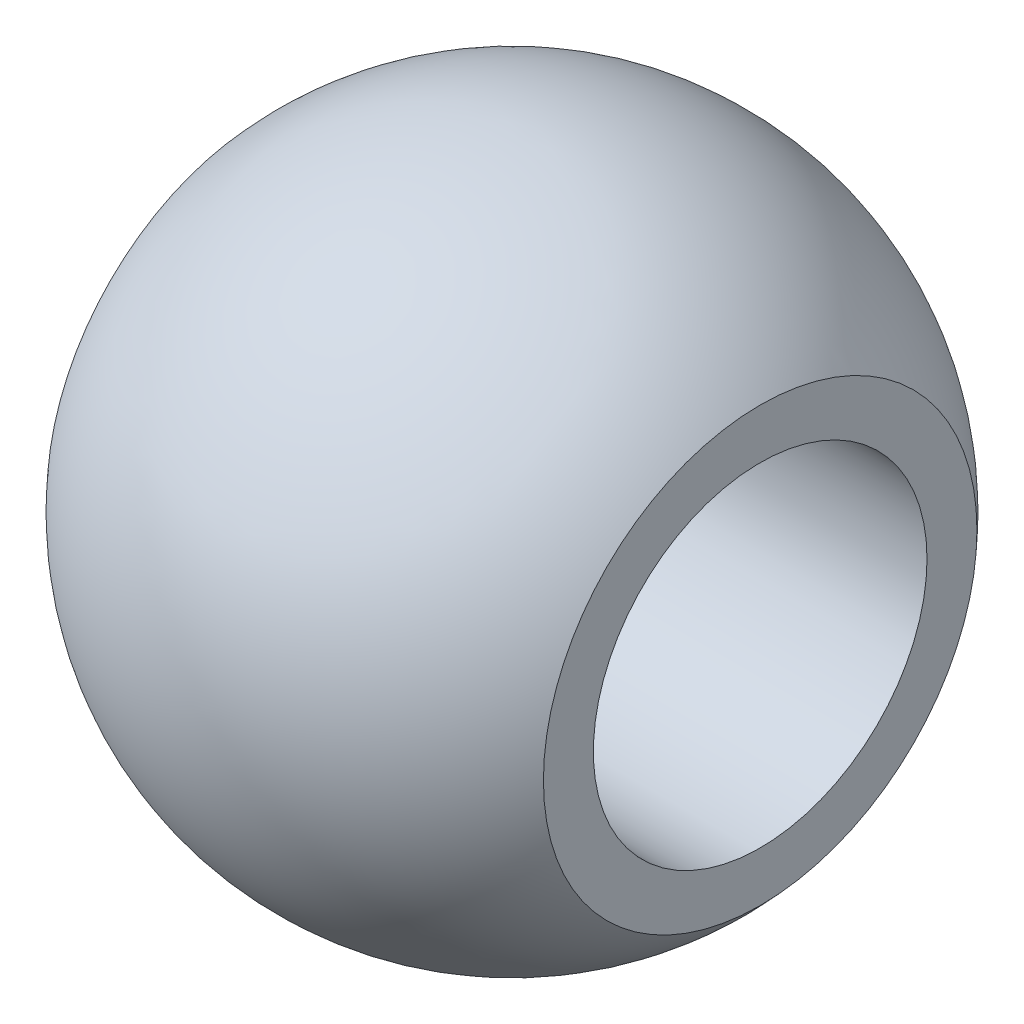
SolidWorks part; units mm, degrees
ref_plane "Front Plane" through (0, 0, 0) normal (0, 0, 1) x (1, 0, 0)
ref_plane "Top Plane" through (0, 0, 0) normal (0, 1, 0) x (1, 0, 0)
ref_plane "Right Plane" through (0, 0, 0) normal (1, 0, 0) x (0, 0, -1)
sketch "Sketch1" plane through (0, 0, 0) normal (1, 0, 0) x (0, 0, -1)
  line L0 (0, -7.9) -> (0, 0)
  line L1 (0, 0) -> (0, 7.9)
  arc A0 (0, 7.9) -> (0, -7.9) centre (0, 0) ccw
  dimension "D1" = 15.8
revolve "Revolve1" add sketch "Sketch1" angle 360 about L1
ref_plane "Plane1" through (5.95, 0, 0) normal (1, 0, 0) x (0, 0, -1)
ref_plane "Plane2" through (-5.95, 0, 0) normal (1, 0, 0) x (0, 0, -1)
other "SurfaceCut1"
other "SurfaceCut2"
sketch "Sketch3" plane through (-5.95, 0, 0) normal (1, 0, 0) x (0, 0, -1)
  circle A0 centre (0, 0) radius 4
  dimension "D1" = 8
extrude "Cut-Extrude2" cut sketch "Sketch3" along normal up to next
ref_point "Point2"
